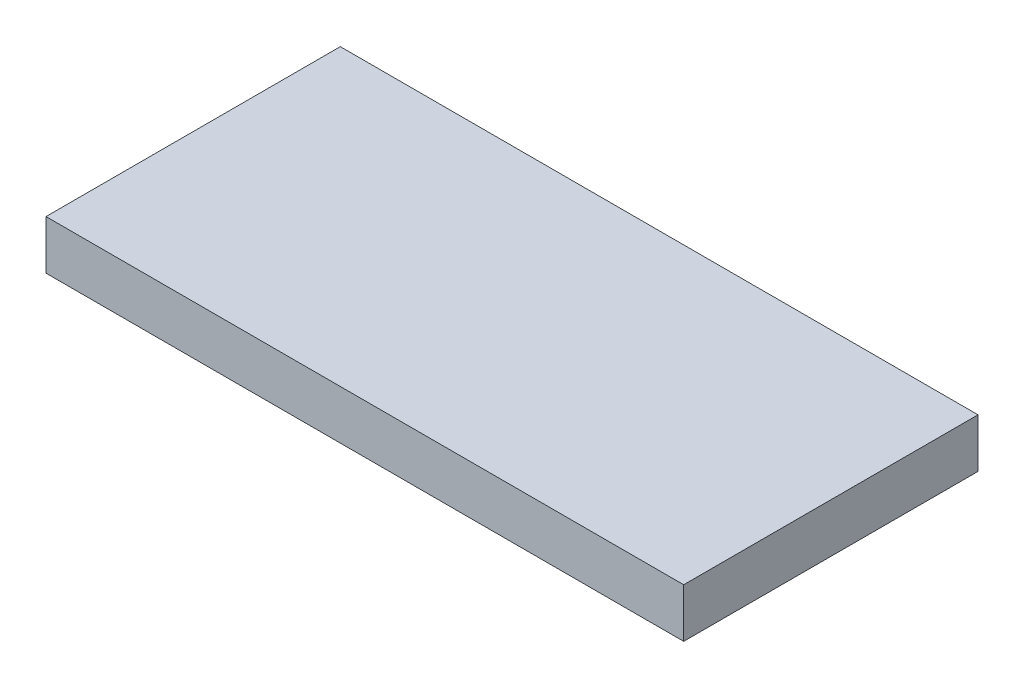
SolidWorks part; units mm, degrees
ref_plane "Front Plane" through (0, 0, 0) normal (0, 0, 1) x (1, 0, 0)
ref_plane "Top Plane" through (0, 0, 0) normal (0, 1, 0) x (1, 0, 0)
ref_plane "Right Plane" through (0, 0, 0) normal (1, 0, 0) x (0, 0, -1)
sketch "Sketch1" plane through (0, 0, 0) normal (0, 1, 0) x (1, 0, 0)
  line L1 (0, 0) -> (-65, 0)
  line L2 (0, 0) -> (0, -30)
  line L3 (0, -30) -> (-65, -30)
  line L4 (-65, 0) -> (-65, -30)
  dimension "D1" = 65
  dimension "D2" = 30
extrude "Boss-Extrude1" add sketch "Sketch1" along normal blind 5
equation "\"alto\"=0.5"
equation "\"D1@Boss-Extrude1\"=\"alto\""
equation "\"ancho\"=3"
equation "\"D2@Sketch1\"=\"ancho\""
equation "\"largo\"=6.5"
equation "\"D1@Sketch1\"=\"largo\""
